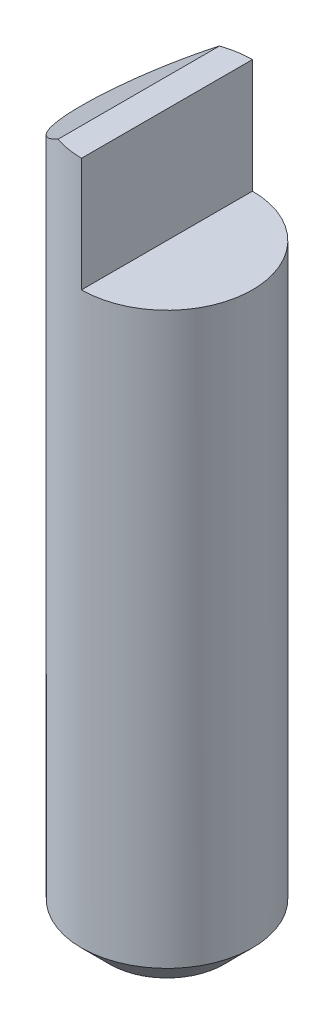
SolidWorks part; units mm, degrees
ref_plane "前视基准面" through (0, 0, 0) normal (0, 0, 1) x (1, 0, 0)
ref_plane "上视基准面" through (0, 0, 0) normal (0, 1, 0) x (1, 0, 0)
ref_plane "右视基准面" through (0, 0, 0) normal (1, 0, 0) x (0, 0, -1)
sketch "草图1" plane through (0, 0, 0) normal (0, 1, 0) x (1, 0, 0)
  circle A0 centre (0, 0) radius 3
  dimension "D1" = 6
extrude "凸台-拉伸1" add sketch "草图1" along normal blind 25
chamfer "倒角1" distance 1 angle 45 1 edges at (0, 0, 3)
sketch "草图2" plane through (0, 0, 0) normal (0, 0, 1) x (1, 0, 0)
  line L0 (-3, 23.6) -> (-0.9907, 25)
  line L1 (-3, 25) -> (-3, 1) construction
  line L2 (3, 25) -> (-3, 25) construction
  line L3 (3.3, 0) -> (-3.3, 0) construction
  line L4 (0, -3.3) -> (0, 3.3) construction
  dimension "D1" = 23.6
  dimension "D2" = 55.133
extrude "切除-拉伸1" cut sketch "草图2" against normal through all and the other way through all
sketch "草图3" plane through (0, 0, 0) normal (0, 0, 1) x (1, 0, 0)
  line L0 (0, 25) -> (0, 21)
  line L1 (0, -3.3) -> (0, 3.3) construction
  line L2 (3, 25) -> (-0.9907, 25) construction
  line L3 (0, 21) -> (3, 21)
  line L4 (3, 1) -> (3, 25) construction
  dimension "D1" = 4
extrude "切除-拉伸2" cut sketch "草图3" against normal through all and the other way through all
